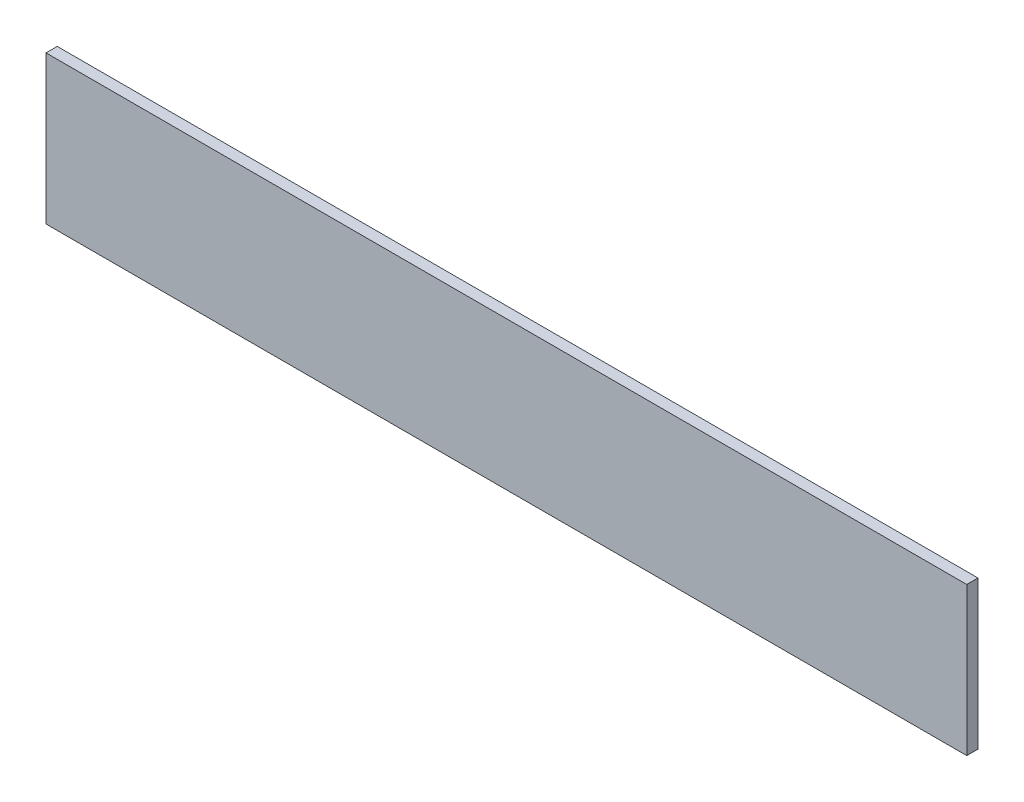
SolidWorks part; units mm, degrees
ref_plane "정면" through (0, 0, 0) normal (0, 0, 1) x (1, 0, 0)
ref_plane "윗면" through (0, 0, 0) normal (0, 1, 0) x (1, 0, 0)
ref_plane "우측면" through (0, 0, 0) normal (1, 0, 0) x (0, 0, -1)
sketch "스케치1" plane through (0, 0, 0) normal (0, 0, 1) x (1, 0, 0)
  line L1 (-205, 33) -> (205, 33)
  line L2 (-205, 33) -> (-205, -33)
  line L3 (-205, -33) -> (205, -33)
  line L4 (205, 33) -> (205, -33)
  line L5 (-205, 33) -> (205, -33) construction
  line L6 (-205, -33) -> (205, 33) construction
  point P0 (0, 0)
  dimension "D1" = 66
  dimension "D2" = 410
extrude "보스-돌출1" add sketch "스케치1" along normal blind 5
